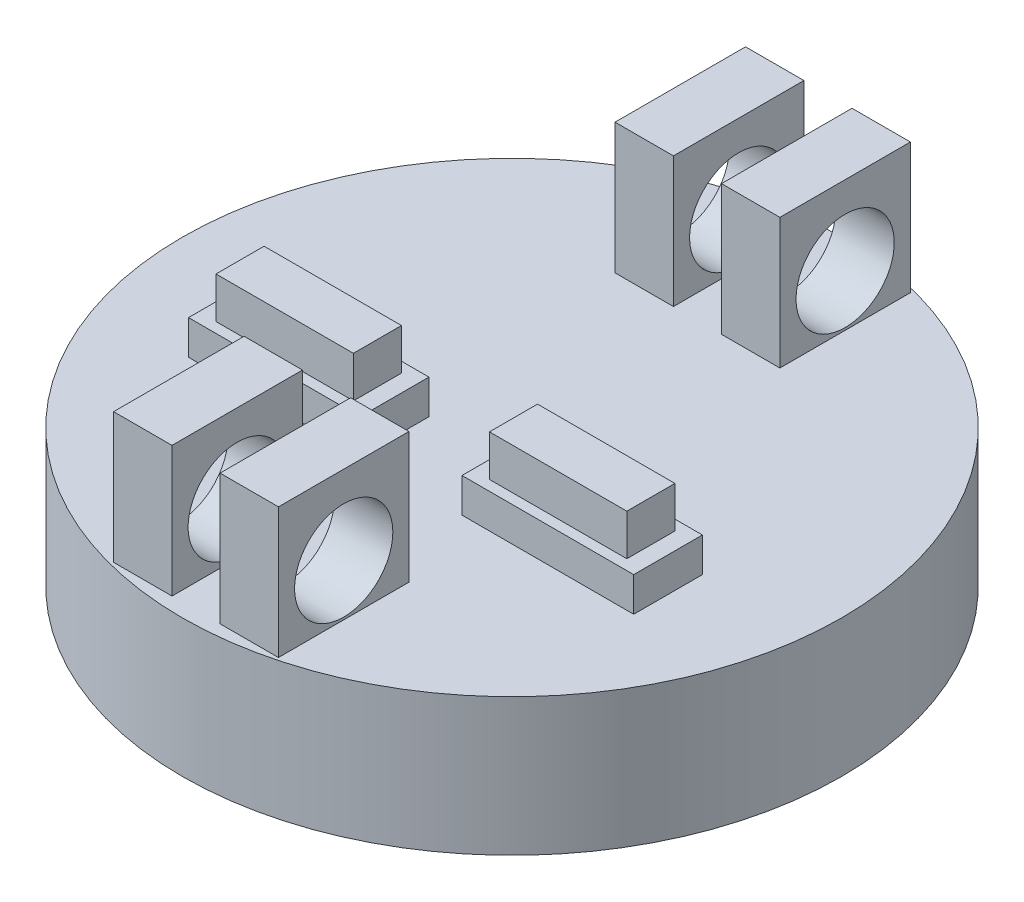
SolidWorks part; units mm, degrees
ref_plane "Front Plane" through (0, 0, 0) normal (0, 0, 1) x (1, 0, 0)
ref_plane "Top Plane" through (0, 0, 0) normal (0, 1, 0) x (1, 0, 0)
ref_plane "Right Plane" through (0, 0, 0) normal (1, 0, 0) x (0, 0, -1)
sketch "Sketch3" plane through (0, 0, 0) normal (0, 1, 0) x (1, 0, 0)
  circle A0 centre (0, 0) radius 48
extrude "Boss-Extrude2" add sketch "Sketch3" along normal blind 20
sketch "Sketch4" plane through (0, 20, 0) normal (0, 1, 0) x (1, 0, 0)
  line L0 (0, 0) -> (-0.9857, 47.9899)
  line L1 (0, 0) -> (0, -48)
  line L2 (0, 0) -> (48.9214, 0)
  line L3 (-0.2502, 0.3128) -> (-47.999, 0.3128)
  line L4 (-32.4058, -9.6872) -> (-7.4058, -9.6872) construction
  line L5 (-32.4058, -4.6872) -> (-7.4058, -4.6872)
  line L6 (-32.4058, -4.6872) -> (-32.4058, -14.6872)
  line L7 (-32.4058, -14.6872) -> (-7.4058, -14.6872)
  line L8 (-7.4058, -4.6872) -> (-7.4058, -14.6872)
  line L9 (7.4058, -4.6872) -> (7.4058, -14.6872)
  line L10 (32.4058, -14.6872) -> (7.4058, -14.6872)
  line L11 (32.4058, -4.6872) -> (32.4058, -14.6872)
  line L12 (32.4058, -4.6872) -> (7.4058, -4.6872)
  circle A0 centre (0, 0) radius 48 construction
  dimension "D1" = 10
  dimension "D2" = 25
  dimension "10" = 10
extrude "Boss-Extrude4" add sketch "Sketch4" along normal blind 5 contours L6 L4 L8 L5 | L4 L6 L7 L8 | L11 L12 L9 L10
sketch "Sketch5" plane through (0, 25, 0) normal (0, 1, 0) x (1, 0, 0)
  line L0 (-32.4058, -9.6872) -> (-7.4058, -9.6872) construction
  line L1 (-32.4058, -4.6872) -> (-32.4058, -14.6872) construction
  line L2 (-7.4058, -4.6872) -> (-7.4058, -14.6872) construction
  line L3 (0, 0) -> (0, -48)
  line L4 (-29.9058, -13.1872) -> (-9.9058, -13.1872)
  line L5 (-29.9058, -13.1872) -> (-29.9058, -6.1872)
  line L6 (-29.9058, -6.1872) -> (-9.9058, -6.1872)
  line L7 (-9.9058, -13.1872) -> (-9.9058, -6.1872)
  line L8 (-29.9058, -13.1872) -> (-9.9058, -6.1872) construction
  line L9 (-29.9058, -6.1872) -> (-9.9058, -13.1872) construction
  line L10 (29.9058, -13.1872) -> (29.9058, -6.1872)
  line L11 (29.9058, -13.1872) -> (9.9058, -13.1872)
  line L12 (9.9058, -13.1872) -> (9.9058, -6.1872)
  line L13 (29.9058, -6.1872) -> (9.9058, -6.1872)
  circle A0 centre (0, 0) radius 48 construction
  point P6 (-19.9058, -9.6872)
  dimension "D1" = 7
  dimension "D2" = 20
extrude "Boss-Extrude5" add sketch "Sketch5" along normal blind 6 contours L10 L13 L12 L11 | L6 L7 L4 L5
sketch "Sketch6" plane through (0, 20, 0) normal (0, 1, 0) x (1, 0, 0)
  line L0 (-12, -46) -> (12, -46)
  line L1 (12, -46) -> (12, -27)
  line L2 (12, -27) -> (-12, -27)
  line L3 (-12, -27) -> (-12, -46)
  line L4 (-48, 0) -> (48, 0)
  line L5 (-12, 27) -> (-12, 46)
  line L6 (12, 46) -> (12, 27)
  line L7 (12, 27) -> (-12, 27)
  line L8 (-12, 46) -> (12, 46)
  circle A0 centre (0, 0) radius 48 construction
  dimension "D1" = 19
extrude "Boss-Extrude6" add sketch "Sketch6" along normal blind 19 contours L2 L3 L0 L1 | L8 L5 L7 L6
sketch "Sketch7" plane through (12, 0, 0) normal (1, 0, 0) x (0, 0, -1)
  circle A0 centre (-36.5, 27.5) radius 7.15
  circle A1 centre (36.5, 27.5) radius 7.15
extrude "Cut-Extrude1" cut sketch "Sketch7" against normal blind 28
sketch "Sketch8" plane through (0, 39, 0) normal (0, 1, 0) x (1, 0, 0)
  line L0 (0, -46) -> (0, -27)
  line L1 (-12, -46) -> (12, -46) construction
  line L2 (12, -27) -> (-12, -27) construction
  line L3 (-25.7892, 0) -> (25.3776, 0)
  line L4 (3.5, -46) -> (-3.5, -46)
  line L5 (3.5, -46) -> (3.5, -27)
  line L6 (3.5, -27) -> (-3.5, -27)
  line L7 (-3.5, -46) -> (-3.5, -27)
  line L8 (3.5, -46) -> (-3.5, -27) construction
  line L9 (3.5, -27) -> (-3.5, -46) construction
  line L10 (3.5, 27) -> (-3.5, 27)
  line L11 (3.5, 46) -> (3.5, 27)
  line L12 (3.5, 46) -> (-3.5, 46)
  line L13 (-3.5, 46) -> (-3.5, 27)
  point P6 (0, -36.5)
  line M6 (12, -27) -> (-12, -27)
  line M8 (-12, -46) -> (12, -46)
  dimension "D1" = 19
  dimension "D2" = 7
extrude "Cut-Extrude2" cut sketch "Sketch8" against normal blind 19 contours L7 L0 M8 M6 | L5 L0 M8 M6 | L12 L13 L10 L11
